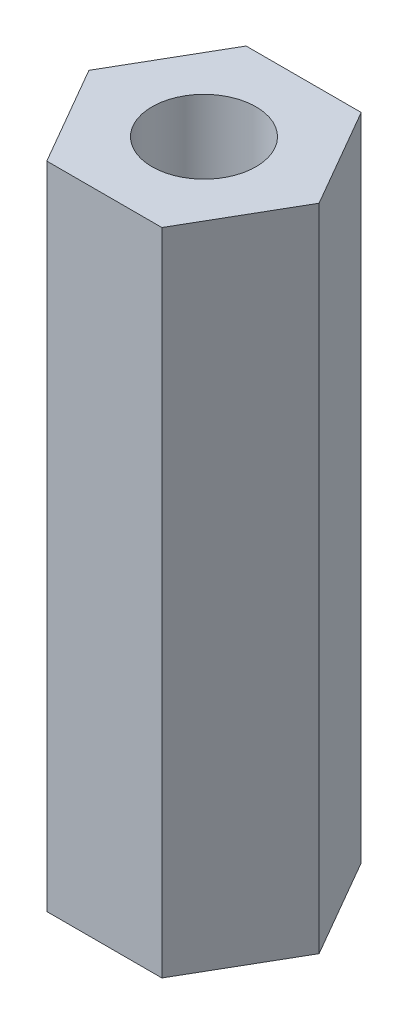
SolidWorks part; units mm, degrees
ref_plane "前视基准面" through (0, 0, 0) normal (0, 0, 1) x (1, 0, 0)
ref_plane "上视基准面" through (0, 0, 0) normal (0, 1, 0) x (1, 0, 0)
ref_plane "右视基准面" through (0, 0, 0) normal (1, 0, 0) x (0, 0, -1)
other "Configuration Table"
sketch "草图1" plane through (0, 0, 0) normal (0, 1, 0) x (1, 0, 0)
  line L1 (2.6558, 0) -> (1.3279, 2.3)
  line L2 (1.3279, 2.3) -> (-1.3279, 2.3)
  line L3 (-1.3279, 2.3) -> (-2.6558, 0)
  line L4 (-2.6558, 0) -> (-1.3279, -2.3)
  line L5 (-1.3279, -2.3) -> (1.3279, -2.3)
  line L6 (1.3279, -2.3) -> (2.6558, 0)
  circle A0 centre (0, 0) radius 2.3 construction
  circle A1 centre (0, 0) radius 1.2
  dimension "D2" = 2.4
  dimension "D1" = 4.6
extrude "凸台-拉伸1" add sketch "草图1" along normal blind 15
